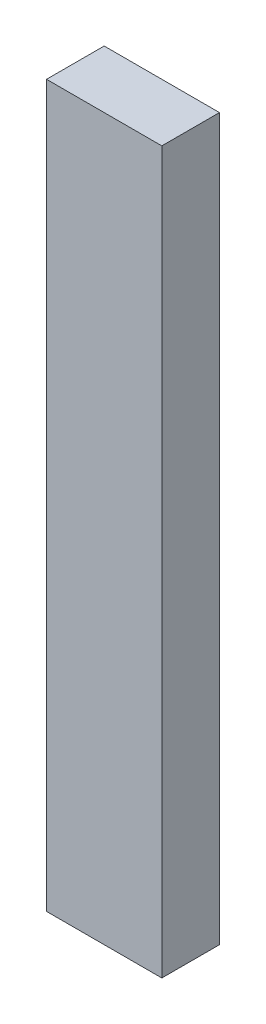
SolidWorks part; units mm, degrees
ref_plane "Спереди" through (0, 0, 0) normal (0, 0, 1) x (1, 0, 0)
ref_plane "Сверху" through (0, 0, 0) normal (0, 1, 0) x (1, 0, 0)
ref_plane "Справа" through (0, 0, 0) normal (1, 0, 0) x (0, 0, -1)
sketch "Эскиз1" plane through (0, 0, 0) normal (0, 1, 0) x (1, 0, 0)
  line L1 (0, 0) -> (40, 0)
  line L2 (0, 0) -> (0, 20)
  line L3 (0, 20) -> (40, 20)
  line L4 (40, 0) -> (40, 20)
  dimension "D1" = 20
  dimension "D2" = 40
extrude "Бобышка-Вытянуть1" add sketch "Эскиз1" along normal blind 250
